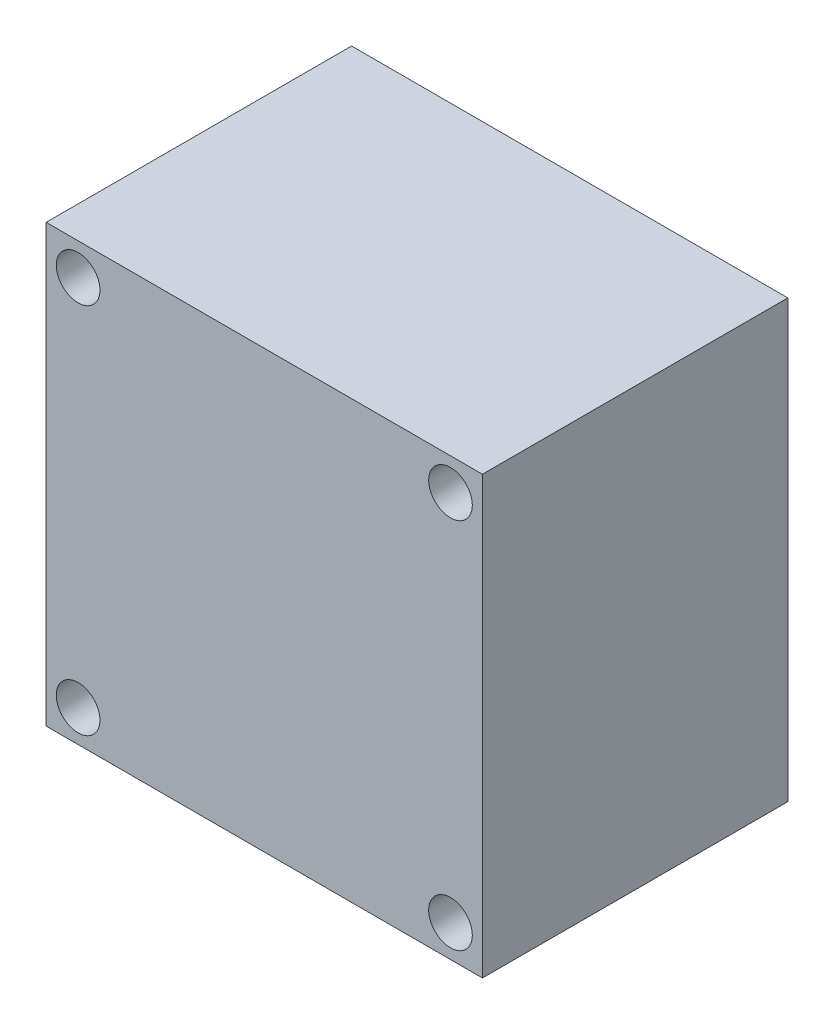
SolidWorks part; units mm, degrees
material "Custom Plastic"
ref_plane "X-Y Datum" through (0, 0, 0) normal (0, 0, 1) x (1, 0, 0)
ref_plane "X-Z Datum" through (0, 0, 0) normal (0, 1, 0) x (1, 0, 0)
ref_plane "Y-Z Datum" through (0, 0, 0) normal (1, 0, 0) x (0, 0, -1)
sketch "Sketch1" plane through (0, 0, 0) normal (0, 0, 1) x (1, 0, 0)
  line L1 (-20, 20) -> (20, 20)
  line L2 (-20, 20) -> (-20, -20)
  line L3 (-20, -20) -> (20, -20)
  line L4 (20, 20) -> (20, -20)
  line L5 (-20, 20) -> (20, -20) construction
  line L6 (-20, -20) -> (20, 20) construction
  point P0 (0, 0)
  dimension "D1" = 40
  dimension "D2" = 40
extrude "Boss-Extrude1" add sketch "Sketch1" along normal blind 28
sketch "Sketch2" plane through (0, 0, 28) normal (0, 0, 1) x (1, 0, 0)
  line L0 (0, 0) -> (-14.1421, 14.1421) construction
  line L5 (8.2843, 20) -> (-8.2843, 20) construction
  line L6 (-8.2843, 20) -> (-20, 8.2843) construction
  line L7 (-20, 8.2843) -> (-20, -8.2843) construction
  line L8 (-20, -8.2843) -> (-8.2843, -20) construction
  line L9 (-8.2843, -20) -> (8.2843, -20) construction
  line L10 (8.2843, -20) -> (20, -8.2843) construction
  line L11 (20, -8.2843) -> (20, 8.2843) construction
  line L12 (20, 8.2843) -> (8.2843, 20) construction
  line L13 (-14.1421, 14.1421) -> (-20, 20) construction
  line L14 (-20, 20) -> (-20, -20) construction
  line L15 (0, 0) -> (-14.1421, -14.1421) construction
  line L16 (-14.1421, -14.1421) -> (-20, -20) construction
  line L17 (-20, -20) -> (20, -20) construction
  line L18 (0, 0) -> (14.1421, 14.1421) construction
  line L19 (14.1421, 14.1421) -> (20, 20) construction
  line L20 (20, 20) -> (-20, 20) construction
  line L21 (0, 0) -> (14.1421, -14.1421) construction
  line L22 (14.1421, -14.1421) -> (20, -20) construction
  line L23 (20, -20) -> (20, 20) construction
  circle A4 centre (0, 0) radius 20 construction
  circle A5 centre (-17.0711, 17.0711) radius 2
  circle A6 centre (-17.0711, -17.0711) radius 2
  circle A7 centre (17.0711, 17.0711) radius 2
  circle A8 centre (17.0711, -17.0711) radius 2
  point P0 (0, 0)
  dimension "D1" = 40
  dimension "D4" = 4
  dimension "D5" = 4
  dimension "D6" = 4
  dimension "D3" = 4
  dimension "D2" = 40
extrude "Cut-Extrude1" cut sketch "Sketch2" against normal through all
